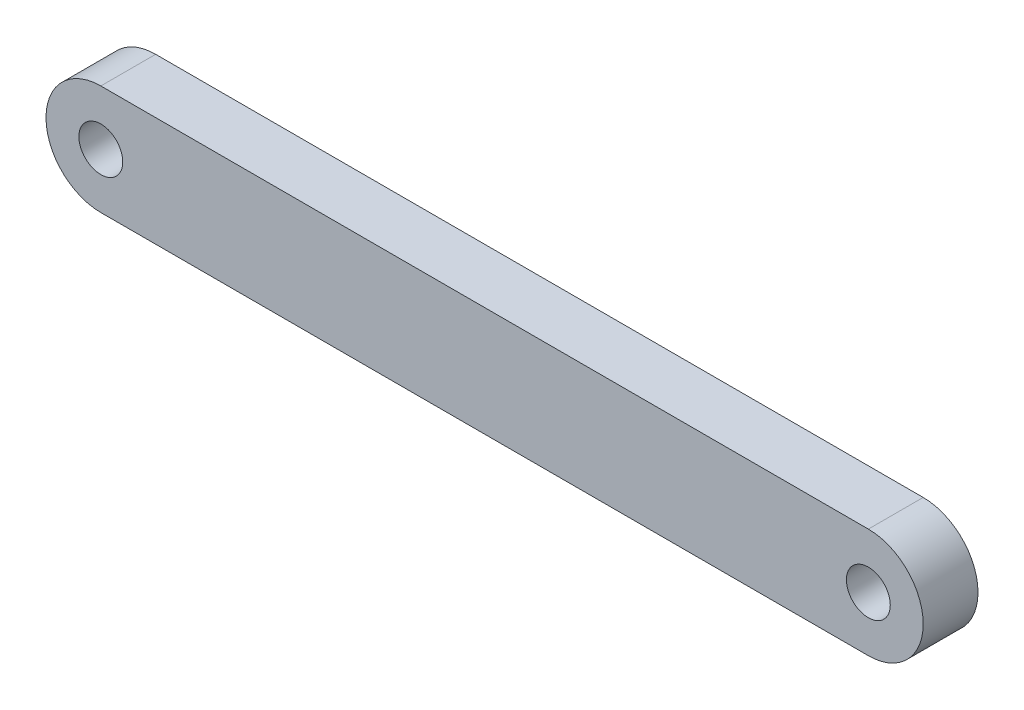
SolidWorks part; units mm, degrees
material "AISI 316 Stainless Steel Sheet (SS)"
ref_plane "Front Plane" through (0, 0, 0) normal (0, 0, 1) x (1, 0, 0)
ref_plane "Top Plane" through (0, 0, 0) normal (0, 1, 0) x (1, 0, 0)
ref_plane "Right Plane" through (0, 0, 0) normal (1, 0, 0) x (0, 0, -1)
sketch "Sketch1" plane through (0, 0, 0) normal (0, 0, 1) x (1, 0, 0)
  line L0 (-70, 0) -> (70, 0) construction
  line L1 (-70, 10) -> (70, 10)
  line L2 (-70, -10) -> (70, -10)
  arc A0 (-70, 10) -> (-70, -10) centre (-70, 0) ccw
  arc A1 (70, -10) -> (70, 10) centre (70, 0) ccw
  point P2 (0, 0)
  dimension "D1" = 20
  dimension "D2" = 140
extrude "Boss-Extrude1" add sketch "Sketch1" along normal mid plane 10
hole_wizard "Ø8.0mm Dowel Hole1" positions "Sketch2" profile "Sketch3" hole size "Ø8.0" standard "ISO" end condition through all
sketch "Sketch2" plane through (0, 0, 5) normal (0, 0, 1) x (1, 0, 0)
  point P0 (-70, 0)
  point P3 (70, 0)
sketch "Sketch3" plane through (-70, 0, 5) normal (1, 0, 0) x (0, -1, 0)
  line L0 (0, 0) -> (0, 10)
  line L1 (0, 10) -> (4, 10)
  line L2 (4, 10) -> (4, 0)
  line L5 (4, 0) -> (0, 0)
  line L11 (0, -6.35) -> (0, 107.95) construction
  dimension "Thru Hole Dia." = 8
  dimension "Thru Hole Depth" = 10
ref_point "Point1"
ref_point "Point2"
sketch "Sketch4" plane through (0, 0, 5) normal (0, 0, 1) x (1, 0, 0)
  point P0 (-70, 0)
